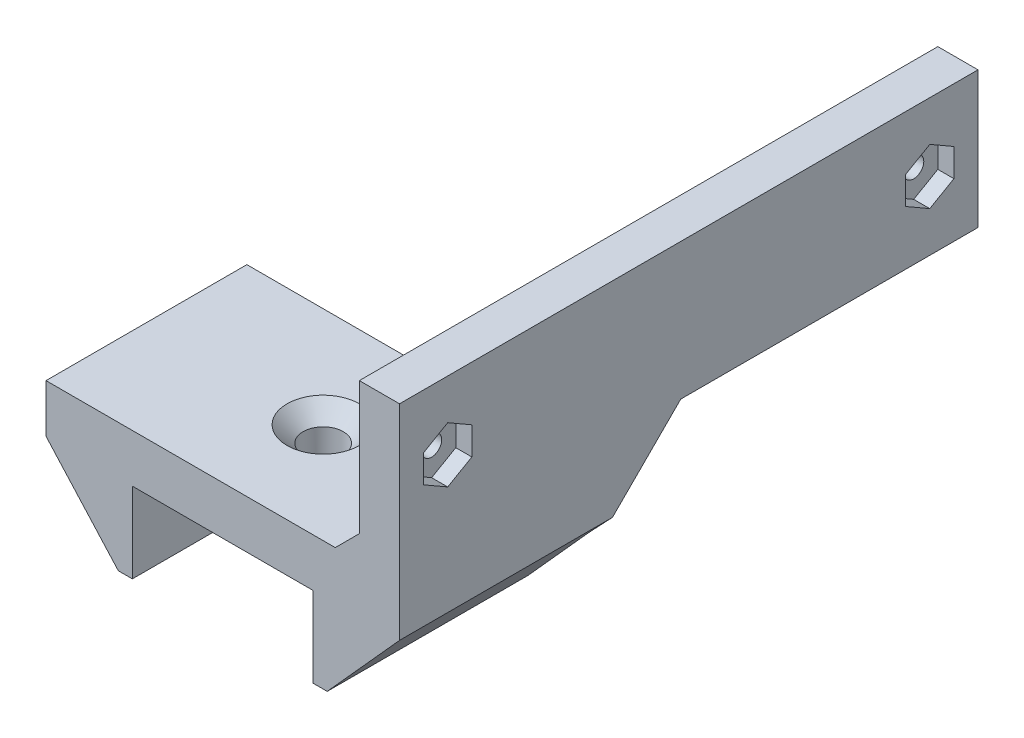
SolidWorks part; units mm, degrees
ref_plane "Top Plane" through (0, 0, 0) normal (0, 0, 1) x (1, 0, 0)
ref_plane "Right Plane" through (0, 0, 0) normal (0, 1, 0) x (1, 0, 0)
ref_plane "Front Plane" through (0, 0, 0) normal (1, 0, 0) x (0, 0, -1)
sketch "Sketch1" plane through (0, 0, 0) normal (0, 0, 1) x (1, 0, 0)
  line L0 (-11.25, 0) -> (11.25, 0)
  line L1 (11.25, 0) -> (11.25, -10)
  line L2 (11.25, -10) -> (13, -10)
  line L3 (13, -10) -> (22, 0)
  line L9 (22, 6) -> (-22, 6)
  line L10 (-22, 6) -> (-22, 0)
  line L11 (-22, 0) -> (-13, -10)
  line L12 (-13, -10) -> (-11.25, -10)
  line L13 (-11.25, -10) -> (-11.25, 0)
  line L14 (-22, 0) -> (-11.25, 0) construction
  line L15 (11.25, 0) -> (22, 0) construction
  line L16 (22, 0) -> (22, 6)
  dimension "D1" = 22.5
  dimension "D2" = 10
  dimension "D3" = 1.75
  dimension "D4" = 44
  dimension "D5" = 6
  dimension "D6" = 6
extrude "Boss-Extrude1" add sketch "Sketch1" along normal blind 25
sketch "Sketch2" plane through (22, 0, 0) normal (1, 0, 0) x (0, 0, -1)
  line L0 (-25, 6) -> (0, 6) construction
  line L3 (-25, 6) -> (0, 6)
  line L4 (0, 8.5) -> (0, 6)
  line L5 (-25, 0) -> (-25, 6) construction
  line L6 (0, 8.5) -> (47, 8.5)
  line L7 (-25, 25.5) -> (47, 25.5)
  line L8 (-25, 25.5) -> (-25, 6)
  line L10 (47, 25.5) -> (47, 8.5)
  line L11 (-19, 17) -> (41, 17) construction
  line L12 (47, 17) -> (41, 17) construction
  line L13 (-19, 17) -> (-25, 17) construction
  circle A0 centre (-19, 17) radius 1.25
  circle A1 centre (41, 17) radius 1.25
  dimension "D2" = 2.5
  dimension "D1" = 60
  dimension "D3" = 11
  dimension "D4" = 17
  dimension "D5" = 6
extrude "Boss-Extrude2" add sketch "Sketch2" against normal blind 5
sketch "Sketch3" plane through (0, 6, 0) normal (0, 1, 0) x (1, 0, 0)
  line L1 (-22, -12.5) -> (22, -12.5) construction
  line L2 (-22, -25) -> (-22, 0) construction
  line L3 (22, -25) -> (22, 0) construction
  circle A0 centre (0, -12.5) radius 2.5
  dimension "D1" = 5
extrude "Cut-Extrude1" cut sketch "Sketch3" against normal through all
chamfer "Chamfer1" distance 2 angle 45 1 edges at (0, 6, 15)
sketch "Sketch4" plane through (22, 0, 0) normal (1, 0, 0) x (0, 0, -1)
  line L1 (-16, 18.7321) -> (-16, 15.2679)
  line L2 (-16, 15.2679) -> (-19, 13.5359)
  line L3 (-19, 13.5359) -> (-22, 15.2679)
  line L4 (-22, 15.2679) -> (-22, 18.7321)
  line L5 (-22, 18.7321) -> (-19, 20.4641)
  line L6 (-19, 20.4641) -> (-16, 18.7321)
  circle A0 centre (-19, 17) radius 3.4641 construction
  dimension "D1" = 6
extrude "Cut-Extrude2" cut sketch "Sketch4" against normal blind 2
ref_plane "Plane1" through (0, 0, -11) normal (0, 0, 1) x (1, 0, 0)
mirror "Mirror1" about plane through (0, 0, -11) normal (0, 0, 1) of "Cut-Extrude2"
chamfer "Chamfer2" distance 3 angle 45 1 edges at (17, 6, 12.5)
sketch "Sketch5" plane through (0, 8.5, 0) normal (0, -1, 0) x (1, 0, 0)
  line L0 (16.5, 0) -> (22, 0) construction
  line L1 (16.5, -47) -> (17, -47)
  line L2 (16.5, -47) -> (16.5, 0)
  line L3 (16.5, 0) -> (17, 0)
  line L4 (17, -47) -> (17, 0)
extrude "Cut-Extrude3" cut sketch "Sketch5" against normal through all
chamfer "Chamfer3" distance 10 angle 45 1 edges at (19.5, 8.5, 0)
